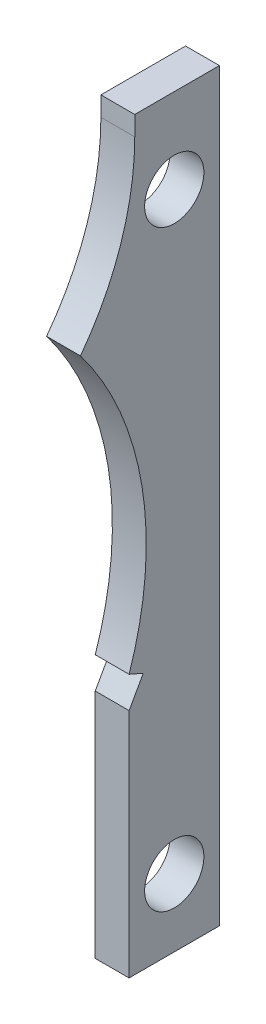
SolidWorks part; units mm, degrees
ref_plane "Front Plane" through (0, 0, 0) normal (0, 0, 1) x (1, 0, 0)
ref_plane "Top Plane" through (0, 0, 0) normal (0, 1, 0) x (1, 0, 0)
ref_plane "Right Plane" through (0, 0, 0) normal (1, 0, 0) x (0, 0, -1)
sketch "Sketch1" plane through (0, 0, 0) normal (1, 0, 0) x (0, 0, -1)
  line L0 (0, 55) -> (0, -55) construction
  line L1 (0, 66) -> (-15, 66)
  line L2 (0, 66) -> (0, -66)
  line L3 (0, -66) -> (-16, -66)
  line L4 (-15, 66) -> (-15, 62.56)
  line L5 (-16, -19.4031) -> (-13.5007, -20.5015)
  line L6 (-16, -24.97) -> (-16, -66)
  line L9 (-13.5007, -20.5015) -> (-16, -24.97)
  arc A1 (-16, -19.4031) -> (-24.621, 33.7655) centre (-70.52, -0.96) ccw
  arc A2 (-24.621, 33.7655) -> (-15, 62.56) centre (-62.9, 62.56) ccw
  dimension "D3" = 115.11
  dimension "D6" = 95.8
  dimension "D9" = 5.12
  dimension "D1" = 15
  dimension "D2" = 132
  dimension "D4" = 66.96
  dimension "D5" = 70.52
  dimension "D7" = 3.44
  dimension "D8" = 5.5669
  dimension "D10" = 41.03
  dimension "D11" = 16
  dimension "D13" = 2.73
extrude "Boss-Extrude1" add sketch "Sketch1" along normal mid plane 6
sketch "Sketch3" plane through (3, 0, 0) normal (1, 0, 0) x (0, 0, -1)
  line L0 (0, 66) -> (-15, 66) construction
  line L1 (0, 3.3) -> (0, -3.3) construction
  circle A0 centre (-8, 51) radius 5.25
  circle A1 centre (-8, -54) radius 5.25
  dimension "D1" = 10.5
  dimension "D2" = 15
  dimension "D3" = 8
  dimension "D4" = 105
extrude "Cut-Extrude1" cut sketch "Sketch3" against normal through all
